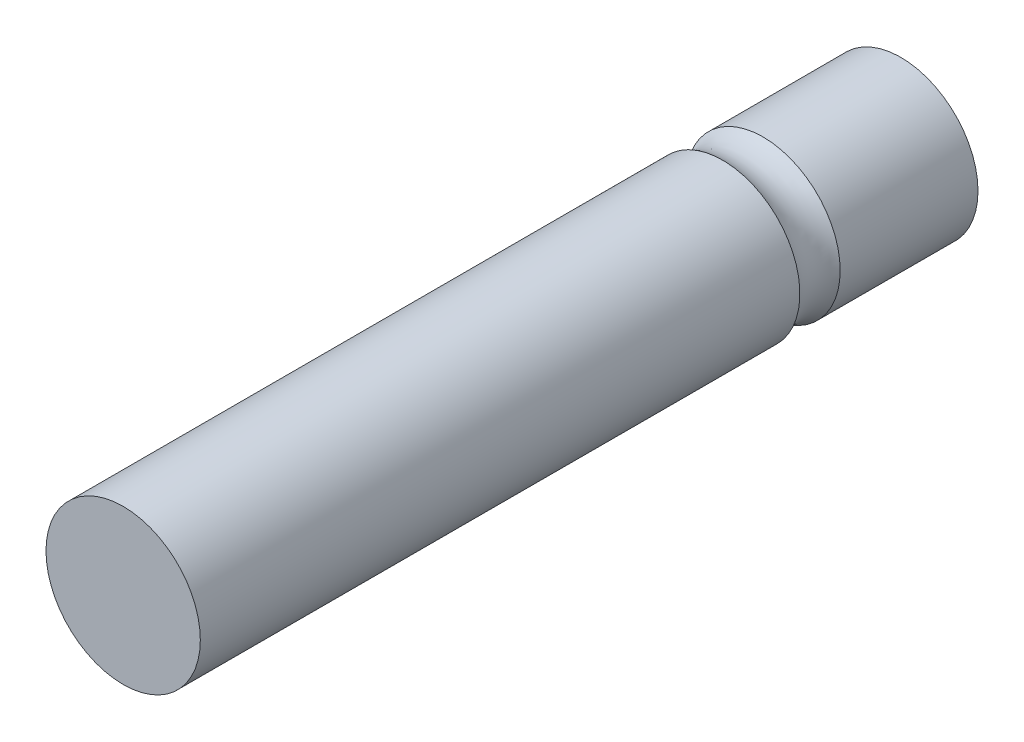
SolidWorks part; units mm, degrees
material "Titanium"
ref_plane "Front Plane" through (0, 0, 0) normal (0, 0, 1) x (1, 0, 0)
ref_plane "Top Plane" through (0, 0, 0) normal (0, 1, 0) x (1, 0, 0)
ref_plane "Right Plane" through (0, 0, 0) normal (1, 0, 0) x (0, 0, -1)
sketch "Sketch1" plane through (0, 0, 0) normal (0, 0, 1) x (1, 0, 0)
  circle A0 centre (0, 0) radius 3.175
  dimension "D1" = 6.35
extrude "Boss-Extrude1" add sketch "Sketch1" along normal blind 32
sketch "Sketch2" plane through (0, 0, 0) normal (1, 0, 0) x (0, 0, -1)
  line L0 (-6.5, 2.925) -> (0, 2.925) construction
  line L1 (0, -3.175) -> (0, 3.175) construction
  line L2 (0, 3.175) -> (-32, 3.175) construction
  circle A0 centre (-6.5, 4.425) radius 1.5
  dimension "D1" = 3
  dimension "D2" = 6.5
  dimension "D3" = 0.25
sketch "Sketch3" plane through (0, 0, 0) normal (1, 0, 0) x (0, 0, -1)
  line L0 (0, 0) -> (-43.3492, 0)
revolve "Cut-Revolve1" cut sketch "Sketch2" angle 360 about L0
